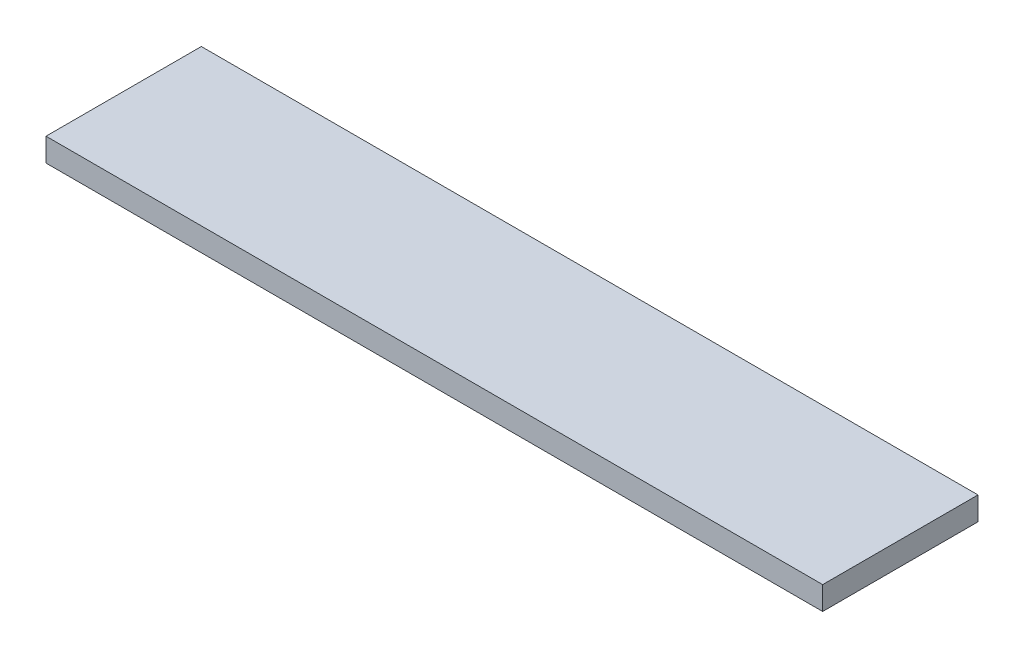
SolidWorks part; units mm, degrees
ref_plane "Plano frontal" through (0, 0, 0) normal (0, 0, 1) x (1, 0, 0)
ref_plane "Plano superior" through (0, 0, 0) normal (0, 1, 0) x (1, 0, 0)
ref_plane "Plano direito" through (0, 0, 0) normal (1, 0, 0) x (0, 0, -1)
sketch "Esboço2" plane through (0, 0, 0) normal (0, 1, 0) x (1, 0, 0)
  line L0 (-44.9194, 10.1796) -> (55.0806, 10.1796)
  line L1 (55.0806, 10.1796) -> (55.0806, -9.8204)
  line L2 (55.0806, -9.8204) -> (-44.9194, -9.8204)
  line L3 (-44.9194, -9.8204) -> (-44.9194, 10.1796)
extrude "Ressalto-extrusão2" add sketch "Esboço2" along normal blind 3 contours L3 L0 L1 L2
